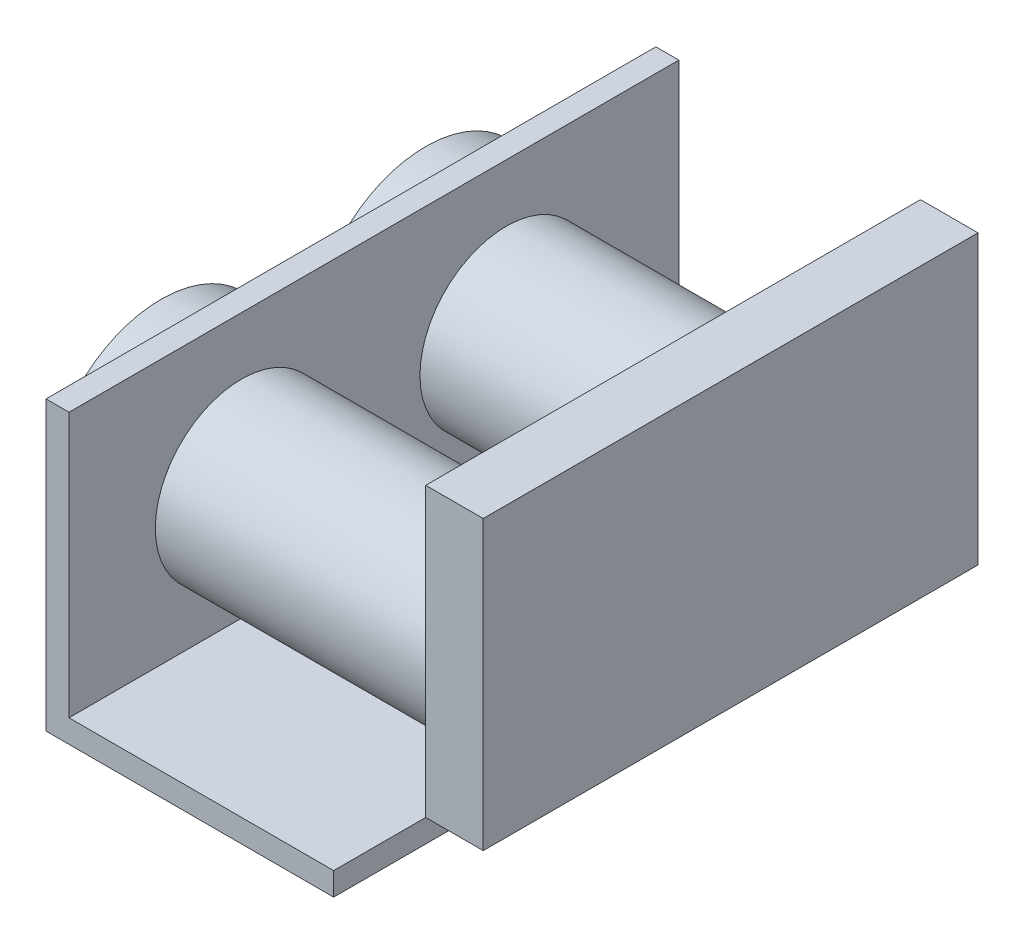
SolidWorks part; units mm, degrees
ref_plane "Front Plane" through (0, 0, 0) normal (0, 0, 1) x (1, 0, 0)
ref_plane "Top Plane" through (0, 0, 0) normal (0, 1, 0) x (1, 0, 0)
ref_plane "Right Plane" through (0, 0, 0) normal (1, 0, 0) x (0, 0, -1)
sketch "Sketch1" plane through (0, 0, 0) normal (0, 0, 1) x (1, 0, 0)
  line L0 (0, 0) -> (25, 0)
  line L1 (55, 0) -> (-55, 0) construction
  line L2 (0, 0) -> (0, 25)
  line L3 (0, -55) -> (0, 55) construction
  dimension "D1" = 25
  dimension "D2" = 25
extrude "Extrude-Thin1" add sketch "Sketch1" along normal blind 53 thin thin type one direction wall 2
sketch "Sketch2" plane through (0, 0, 0) normal (-1, 0, 0) x (0, 0, 1)
  line L0 (0, 12.5) -> (53, 12.5) construction
  line L1 (0, -13.75) -> (0, 13.75) construction
  line L2 (53, 0) -> (53, 25) construction
  circle A0 centre (15, 12.5) radius 10
  circle A1 centre (38, 12.5) radius 10
  dimension "D1" = 20
  dimension "D2" = 15
  dimension "D3" = 15
extrude "Boss-Extrude1" add sketch "Sketch2" along normal blind 5
sketch "Sketch4" plane through (-5, 0, 0) normal (-1, 0, 0) x (0, 0, 1)
  circle A0 centre (38, 12.5) radius 7.5
  circle A1 centre (15, 12.5) radius 7.5
  dimension "D1" = 15
  dimension "D2" = 15
extrude "Boss-Extrude2" add sketch "Sketch4" against normal blind 33
sketch "Sketch5" plane through (28, 0, 0) normal (1, 0, 0) x (0, 0, -1)
  line L0 (18.15, 0) -> (-18.15, 0) construction
  line L1 (-48, 30) -> (-5, 30)
  line L2 (-48, 30) -> (-48, 5)
  line L3 (-48, 5) -> (-5, 5)
  line L4 (-5, 30) -> (-5, 5)
  line L5 (-48, 30) -> (-5, 5) construction
  line L6 (-48, 5) -> (-5, 30) construction
  line L8 (0, 13.75) -> (0, -13.75) construction
  point P0 (-26.5, 17.5)
  dimension "D1" = 25
  dimension "D2" = 43
  dimension "D3" = 5
  dimension "D4" = 26.5
extrude "Boss-Extrude3" add sketch "Sketch5" along normal blind 5
sketch "Sketch6" plane through (0, 0, 0) normal (0, -1, 0) x (1, 0, 0)
  line L0 (0, -16.5) -> (0, 16.5) construction
  line L1 (16.5, 0) -> (-16.5, 0) construction
  circle A0 centre (15, 26.5) radius 1.5
  dimension "D1" = 15
  dimension "D2" = 3
  dimension "D3" = 26.5
extrude "Cut-Extrude1" cut sketch "Sketch6" against normal blind 5
